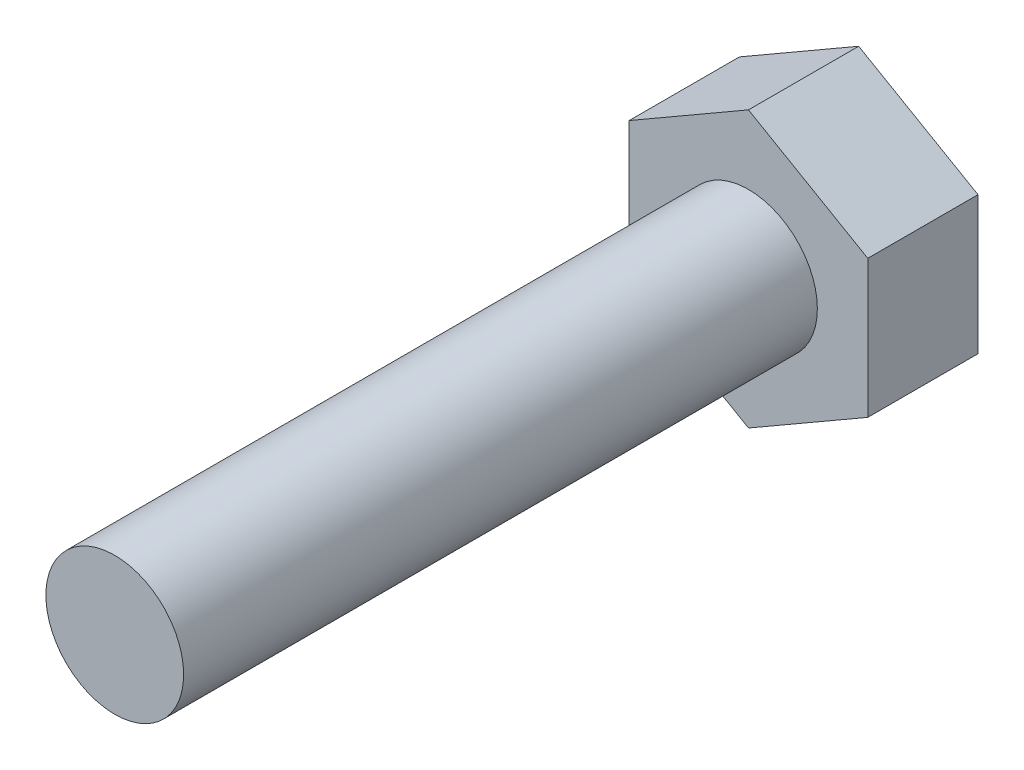
SolidWorks part; units mm, degrees
ref_plane "Plan de face" through (0, 0, 0) normal (0, 0, 1) x (1, 0, 0)
ref_plane "Plan de dessus" through (0, 0, 0) normal (0, 1, 0) x (1, 0, 0)
ref_plane "Plan de droite" through (0, 0, 0) normal (1, 0, 0) x (0, 0, -1)
sketch "Esquisse1" plane through (0, 0, 0) normal (0, 0, 1) x (1, 0, 0)
  circle A0 centre (0, 0) radius 1.25
  circle A1 centre (0, 0) radius 4
  dimension "D1" = 2.5
  dimension "D2" = 8
extrude "Boss.-Extru.1" add sketch "Esquisse1" along normal blind 11.5 contours A0
sketch "Esquisse2" plane through (0, 0, 0) normal (0, 0, -1) x (-1, 0, 0)
  line L0 (0, 0) -> (0, 2.5)
  line L2 (0, 2.5) -> (-2.1651, 1.25)
  line L3 (-2.1651, 1.25) -> (-2.1651, -1.25)
  line L4 (-2.1651, -1.25) -> (0, -2.5)
  line L5 (0, -2.5) -> (2.1651, -1.25)
  line L6 (2.1651, -1.25) -> (2.1651, 1.25)
  line L7 (2.1651, 1.25) -> (0, 2.5)
  circle A0 centre (0, 0) radius 2.1651 construction
  dimension "D1" = 2.5
extrude "Boss.-Extru.2" add sketch "Esquisse2" along normal blind 2
